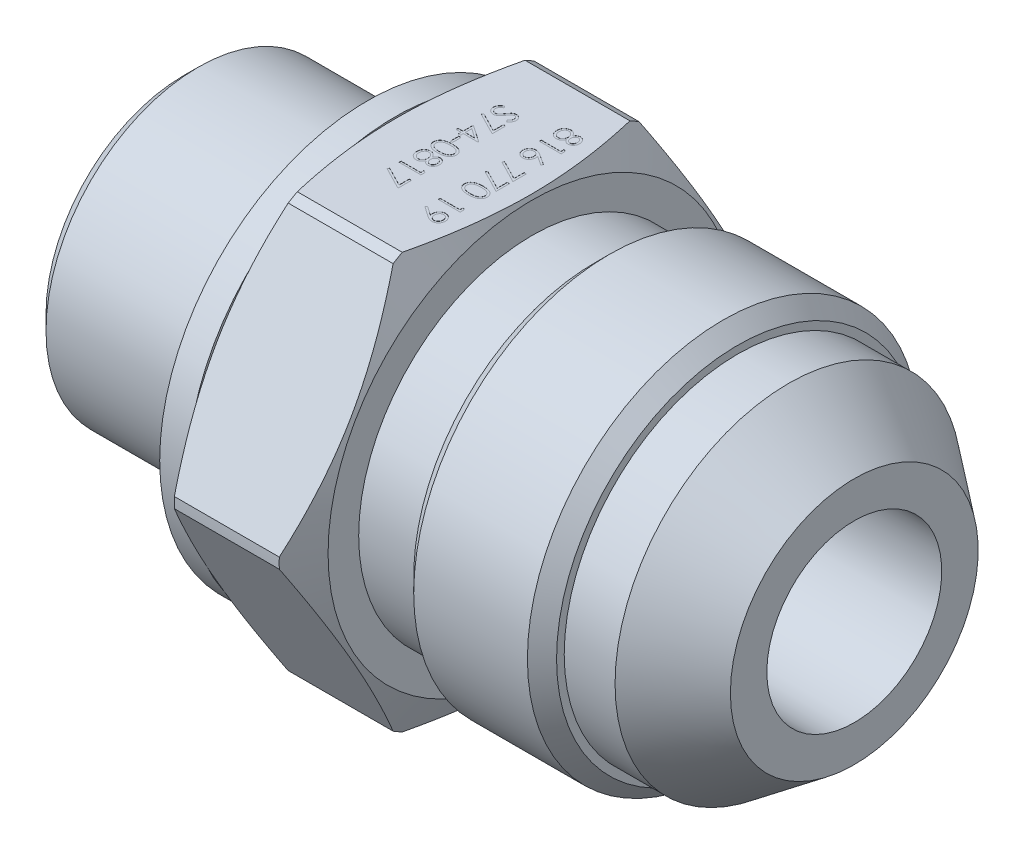
SolidWorks part; units mm, degrees
ref_plane "Front Plane" through (0, 0, 0) normal (0, 0, 1) x (1, 0, 0)
ref_plane "Top Plane" through (0, 0, 0) normal (0, 1, 0) x (1, 0, 0)
ref_plane "Right Plane" through (0, 0, 0) normal (1, 0, 0) x (0, 0, -1)
sketch "Sketch1" plane through (0, 0, 0) normal (0, 0, 1) x (1, 0, 0)
  line L0 (0, 0) -> (53.9967, 0) construction
  line L1 (0, 7.9) -> (0, 10.45)
  line L2 (11.55, 10.45) -> (12.5, 9.5)
  line L3 (0, 10.45) -> (11.55, 10.45)
  line L4 (14.5, 9.5) -> (14.5, 14)
  line L5 (15.6, 16.25) -> (22.8, 16.25)
  line L6 (23.9, 14) -> (23.9, 11.9)
  line L7 (23.9, 11.9) -> (28.2, 11.9)
  line L8 (28.2, 11.9) -> (28.2, 13.425)
  line L9 (28.2, 13.425) -> (38, 13.425)
  line L10 (38, 13.425) -> (38, 11.9)
  line L11 (38, 11.9) -> (41.488, 11.9)
  line L12 (41.488, 11.9) -> (46, 8.5)
  line L13 (46, 8.5) -> (46, 6)
  line L14 (0, 7.9) -> (3.2909, 6)
  line L18 (46, 6) -> (3.2909, 6)
  line L19 (12.5, 9.5) -> (14.5, 9.5)
  line L20 (15.6, 16.25) -> (14.5, 14)
  line L21 (22.8, 16.25) -> (23.9, 14)
  dimension "D1" = 17
  dimension "D3" = 23.8
  dimension "D4" = 37
  dimension "D5" = 8
  dimension "D6" = 26.85
  dimension "D7" = 17.8
  dimension "D8" = 14.5
  dimension "D9" = 46
  dimension "D10" = 4.3
  dimension "D11" = 20.9
  dimension "D12" = 45
  dimension "D13" = 32.5
  dimension "D14" = 28
  dimension "D15" = 1.1
  dimension "D16" = 1.1
  dimension "D17" = 19
  dimension "D18" = 15.8
  dimension "D19" = 30
  dimension "D21" = 12
  dimension "D22" = 2
revolve "Revolve1" add sketch "Sketch1" angle 360 about L0
cosmetic thread "Cosmetic Thread1" parameters "D2"=19.5
cosmetic thread "Cosmetic Thread2" parameters "D2"=24.5
sketch "Sketch2" plane through (23.9, 0, 0) normal (1, 0, 0) x (0, 0, -1)
  line L1 (8.2272, 14.25) -> (-8.2272, 14.25)
  line L2 (-8.2272, 14.25) -> (-16.4545, 0)
  line L3 (-16.4545, 0) -> (-8.2272, -14.25)
  line L4 (-8.2272, -14.25) -> (8.2272, -14.25)
  line L5 (8.2272, -14.25) -> (16.4545, 0)
  line L6 (16.4545, 0) -> (8.2272, 14.25)
  circle A0 centre (0, 0) radius 14.25 construction
  dimension "D1" = 28.5
extrude "Extrude1" cut sketch "Sketch2" against normal up to surface (9.4 mm away) flip side to cut up to face at (14.5, 0, 9.5)
sketch "Sketch3" plane through (14.5, 0, 0) normal (-1, 0, 0) x (0, 0, 1)
  circle A0 centre (0, 0) radius 14.25
  circle A1 centre (0, 0) radius 11.5
  dimension "D1" = 28.5
  dimension "D2" = 23
extrude "Extrude2" add sketch "Sketch3" along normal blind 1.9
chamfer "Chamfer1" distance 1 angle 45 1 edges at (0, 0, 10.45)
chamfer "Chamfer2" distance 1 angle 45 2 edges at (38, 0, 13.425) (28.2, 0, 13.425)
sketch "Sketch4" plane through (0, 14.25, 0) normal (0, 1, 0) x (1, 0, 0)
  line L0 (20.9, 8.5035) -> (20.9, -8.2954) construction
  line L2 (23.9, -11.9) -> (23.9, 11.9) construction
  text T0 "816 770 19\r\nS74-0817" font "Century Gothic" height 1.5
  dimension "D1" = 3
extrude "Cut-Extrude1" cut sketch "Sketch4" against normal blind 0.01
sketch "Sketch5" plane through (0, 0, 0) normal (0, 0, 1) x (1, 0, 0)
  line L0 (0, 0) -> (21.6842, 0) construction
  line L1 (0, 7.9) -> (0, -7.9) construction
  line L2 (14.5, -14.25) -> (14.5, 14.25) construction
  circle A0 centre (13.25, 10.5) radius 1.25
  dimension "D1" = 21
  dimension "D2" = 2.5
revolve "Revolve2" add sketch "Sketch5" angle 360 about L0
